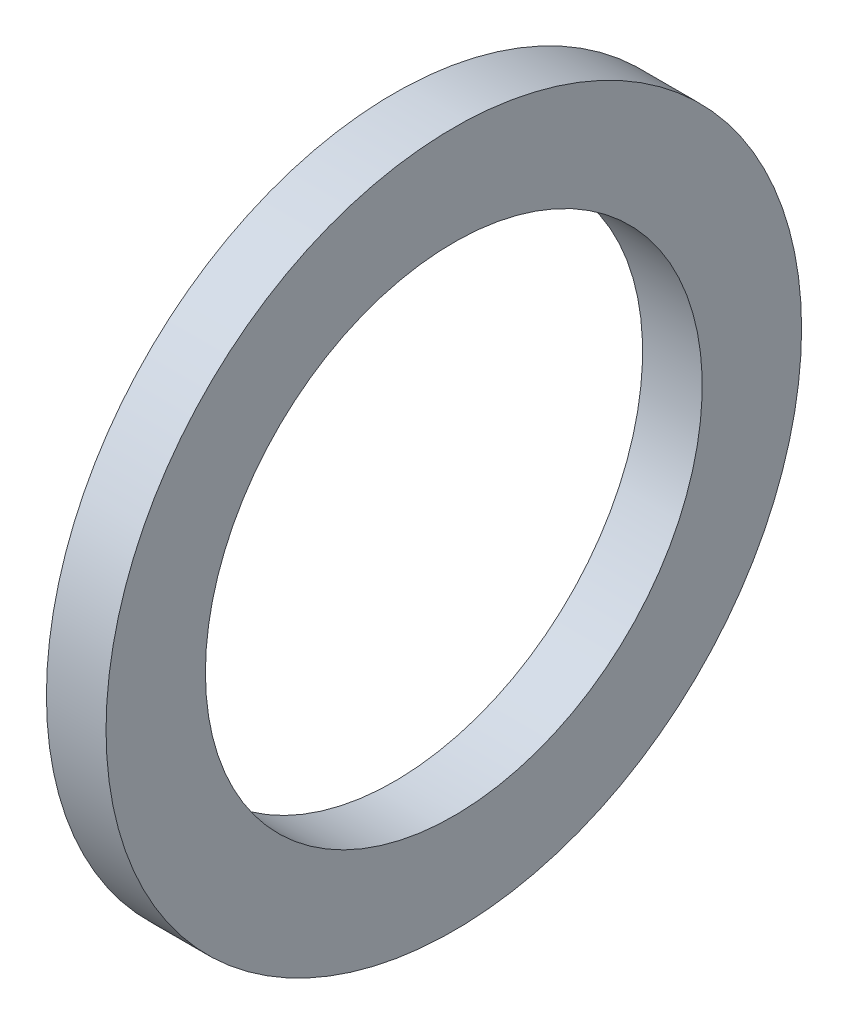
SolidWorks part; units mm, degrees
ref_plane "Front Plane" through (0, 0, 0) normal (0, 0, 1) x (1, 0, 0)
ref_plane "Top Plane" through (0, 0, 0) normal (0, 1, 0) x (1, 0, 0)
ref_plane "Right Plane" through (0, 0, 0) normal (1, 0, 0) x (0, 0, -1)
sketch "Sketch1" plane through (0, 0, 0) normal (1, 0, 0) x (0, 0, -1)
  circle A0 centre (0, 0) radius 3.175
  circle A1 centre (0, 0) radius 4.445
  dimension "D1" = 6.35
  dimension "D2" = 8.89
extrude "Boss-Extrude1" add sketch "Sketch1" along normal blind 0.762
